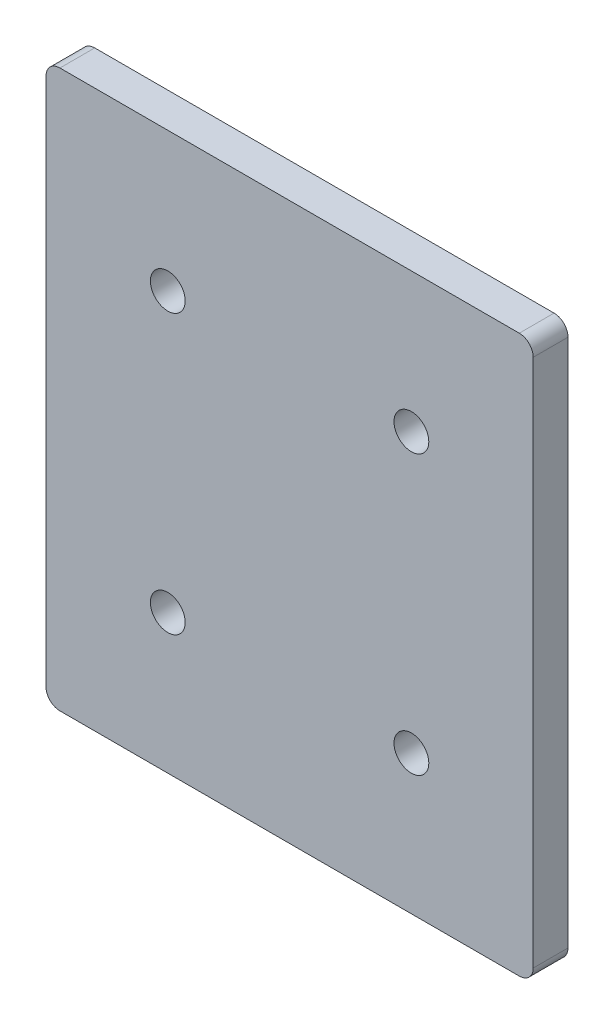
SolidWorks part; units mm, degrees
ref_plane "Front Plane" through (0, 0, 0) normal (0, 0, 1) x (1, 0, 0)
ref_plane "Top Plane" through (0, 0, 0) normal (0, 1, 0) x (1, 0, 0)
ref_plane "Right Plane" through (0, 0, 0) normal (1, 0, 0) x (0, 0, -1)
sketch "Sketch2" plane through (0, 0, 0) normal (0, 0, 1) x (1, 0, 0)
  line L1 (-35, 40) -> (35, 40)
  line L2 (-35, 40) -> (-35, -40)
  line L3 (-35, -40) -> (35, -40)
  line L4 (35, 40) -> (35, -40)
  line L5 (-35, 40) -> (35, -40) construction
  line L6 (-35, -40) -> (35, 40) construction
  circle A0 centre (-17.5, 20) radius 2.5
  circle A2 centre (17.5, 20) radius 2.5
  circle A3 centre (17.5, -20) radius 2.5
  circle A4 centre (-17.5, -20) radius 2.5
  point P0 (0, 0)
  dimension "D3" = 5
  dimension "D1" = 70
  dimension "D2" = 80
  dimension "D4" = 20
  dimension "D5" = 2
  dimension "D6" = 2
extrude "Boss-Extrude1" add sketch "Sketch2" along normal blind 5
fillet "Fillet1" radius 2 4 edges at (-35, -40, 2.5) (35, -40, 2.5) (-35, 40, 2.5) (35, 40, 2.5)
